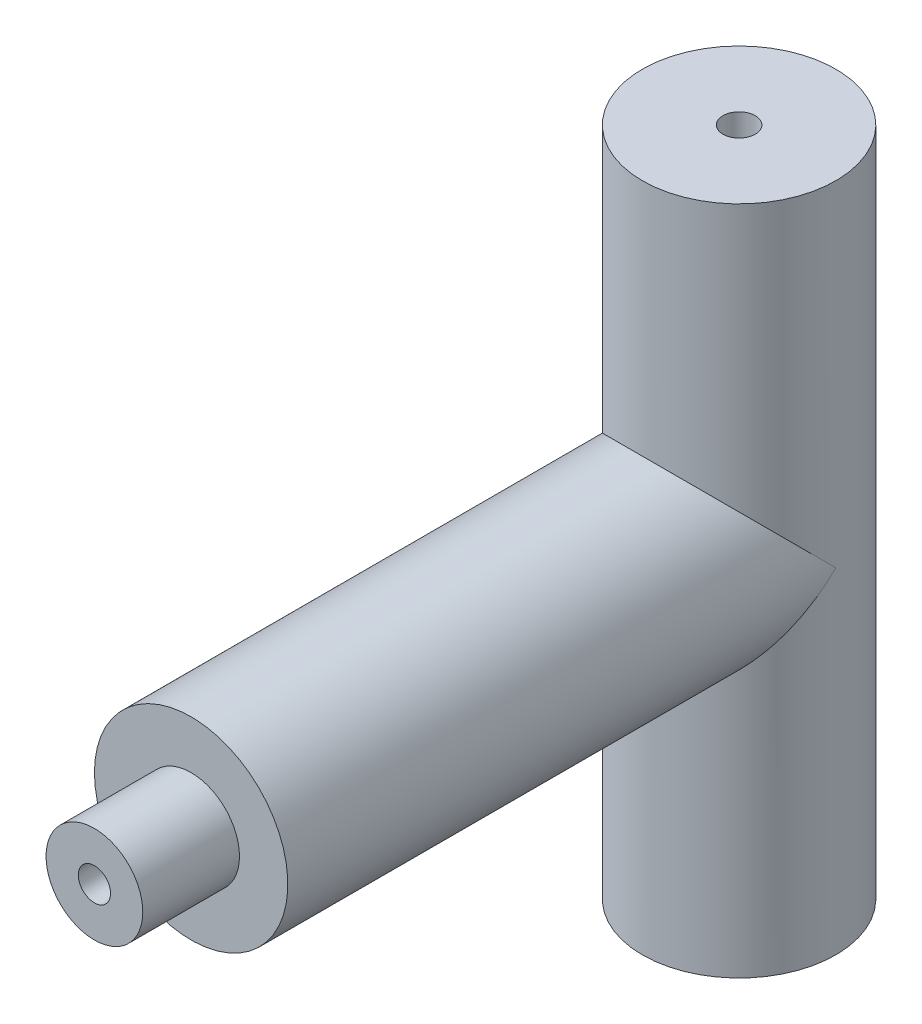
SolidWorks part; units mm, degrees
ref_plane "Front Plane" through (0, 0, 0) normal (0, 0, 1) x (1, 0, 0)
ref_plane "Top Plane" through (0, 0, 0) normal (0, 1, 0) x (1, 0, 0)
ref_plane "Right Plane" through (0, 0, 0) normal (1, 0, 0) x (0, 0, -1)
sketch "Sketch1" plane through (0, 0, 0) normal (0, 0, 1) x (1, 0, 0)
  circle A0 centre (0, 0) radius 7.5
  dimension "D1" = 15
extrude "Boss-Extrude1" add sketch "Sketch1" against normal blind 15
sketch "Sketch2" plane through (0, 0, -15) normal (0, 0, -1) x (-1, 0, 0)
  line L0 (29.8181, 0) -> (-29.6822, 0) construction
  line L2 (0, 31.0543) -> (0, -44.7475) construction
  circle A0 centre (0, 0) radius 15
  point P11 (0, -40)
  dimension "D1" = 30
sketch "Sketch7" plane through (0, 0, 0) normal (0, 0, 1) x (1, 0, 0)
  circle A0 centre (0, 0) radius 2.5
  dimension "D1" = 5
extrude "Cut-Extrude2" cut sketch "Sketch7" against normal blind 5
extrude "Boss-Extrude2" add sketch "Sketch2" along normal blind 100
sketch "Sketch8" plane through (0, 0, 0) normal (0, 1, 0) x (1, 0, 0)
  line L0 (15, 115) -> (-15, 115) construction
  line L2 (15, 165) -> (-15, 165)
  line L3 (15, 165) -> (-15, 165)
  line L4 (-15, 165) -> (-15, 100)
  line L6 (15, 100) -> (15, 165)
  line L7 (-24.8871, 100) -> (26.3808, 100) construction
  line L8 (0, 182.1706) -> (0, 116.5738) construction
  arc A0 (15, 100) -> (-15, 100) centre (0, 100) ccw
  dimension "D1" = 30
  dimension "D2" = 0
extrude "Cut-Extrude3" cut sketch "Sketch8" against normal mid plane 104 contours A0 L3 L4 | A0 L6 L3
sketch "Sketch9" plane through (0, 0, 0) normal (0, 1, 0) x (1, 0, 0)
  circle A0 centre (0, 100) radius 15
  arc A1 (15, 100) -> (-15, 100) centre (0, 100) ccw construction
  dimension "D1" = 30
extrude "Boss-Extrude4" add sketch "Sketch9" along normal mid plane 104
sketch "Sketch10" plane through (0, -52, 0) normal (0, -1, 0) x (1, 0, 0)
  circle A0 centre (0, -100) radius 2.5
  dimension "D1" = 5
extrude "Cut-Extrude4" cut sketch "Sketch10" against normal blind 5
mirror "Mirror1" about plane through (0, 0, 0) normal (0, 1, 0) of "Cut-Extrude4"
